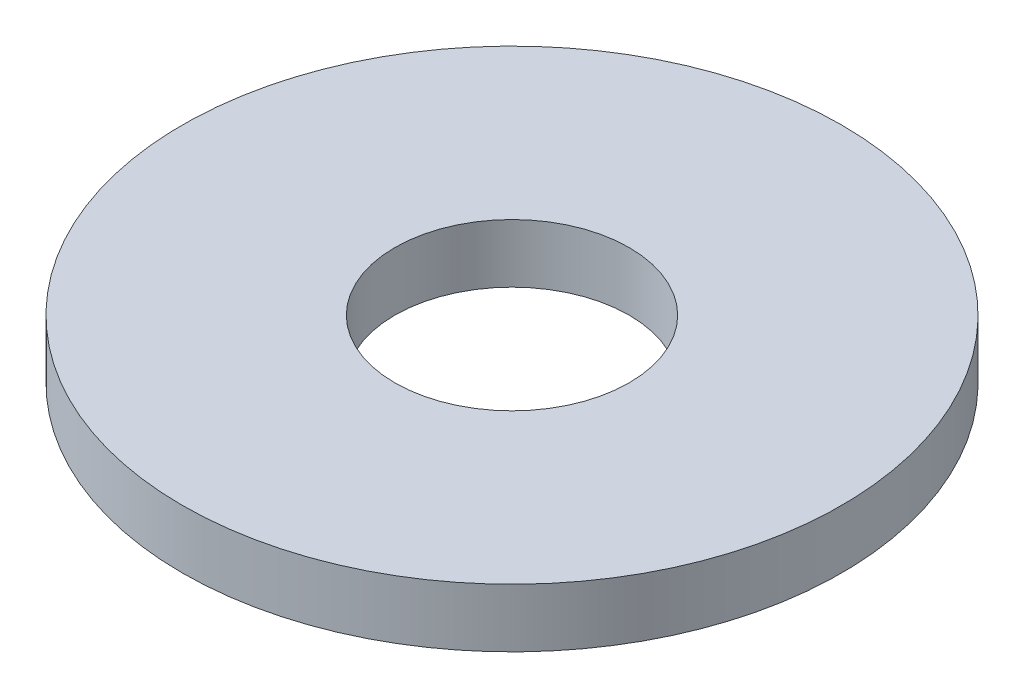
SolidWorks part; units mm, degrees
ref_plane "Спереди" through (0, 0, 0) normal (0, 0, 1) x (1, 0, 0)
ref_plane "Сверху" through (0, 0, 0) normal (0, 1, 0) x (1, 0, 0)
ref_plane "Справа" through (0, 0, 0) normal (1, 0, 0) x (0, 0, -1)
sketch "Эскиз1" plane through (0, 0, 0) normal (0, 1, 0) x (1, 0, 0)
  circle A0 centre (0, 0) radius 3.2
  circle A1 centre (0, 0) radius 9
  dimension "D1" = 6.4
  dimension "D2" = 18
extrude "Вытянуть1" add sketch "Эскиз1" along normal blind 1.6
